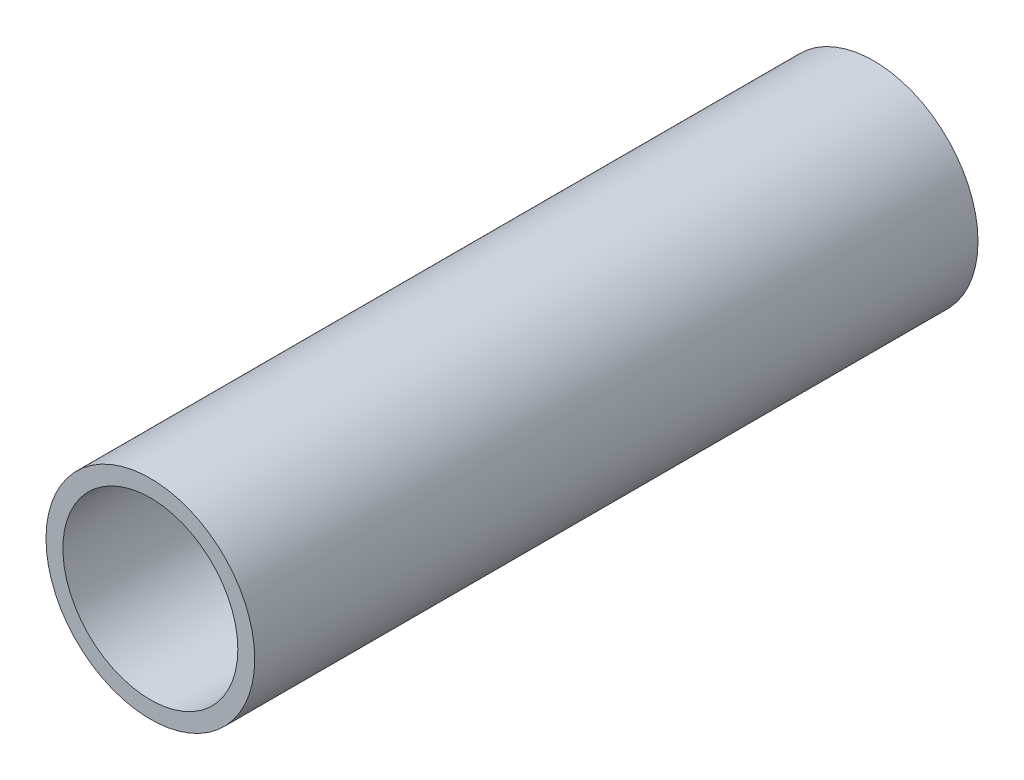
SolidWorks part; units mm, degrees
ref_plane "Front Plane" through (0, 0, 0) normal (0, 0, 1) x (1, 0, 0)
ref_plane "Top Plane" through (0, 0, 0) normal (0, 1, 0) x (1, 0, 0)
ref_plane "Right Plane" through (0, 0, 0) normal (1, 0, 0) x (0, 0, -1)
sketch "Sketch1" plane through (0, 0, 0) normal (0, 0, 1) x (1, 0, 0)
  circle A0 centre (0, 0) radius 30.3
  circle A1 centre (0, 0) radius 25.4
  dimension "D1" = 60.6
  dimension "D2" = 50.8
extrude "Boss-Extrude1" add sketch "Sketch1" along normal blind 210
